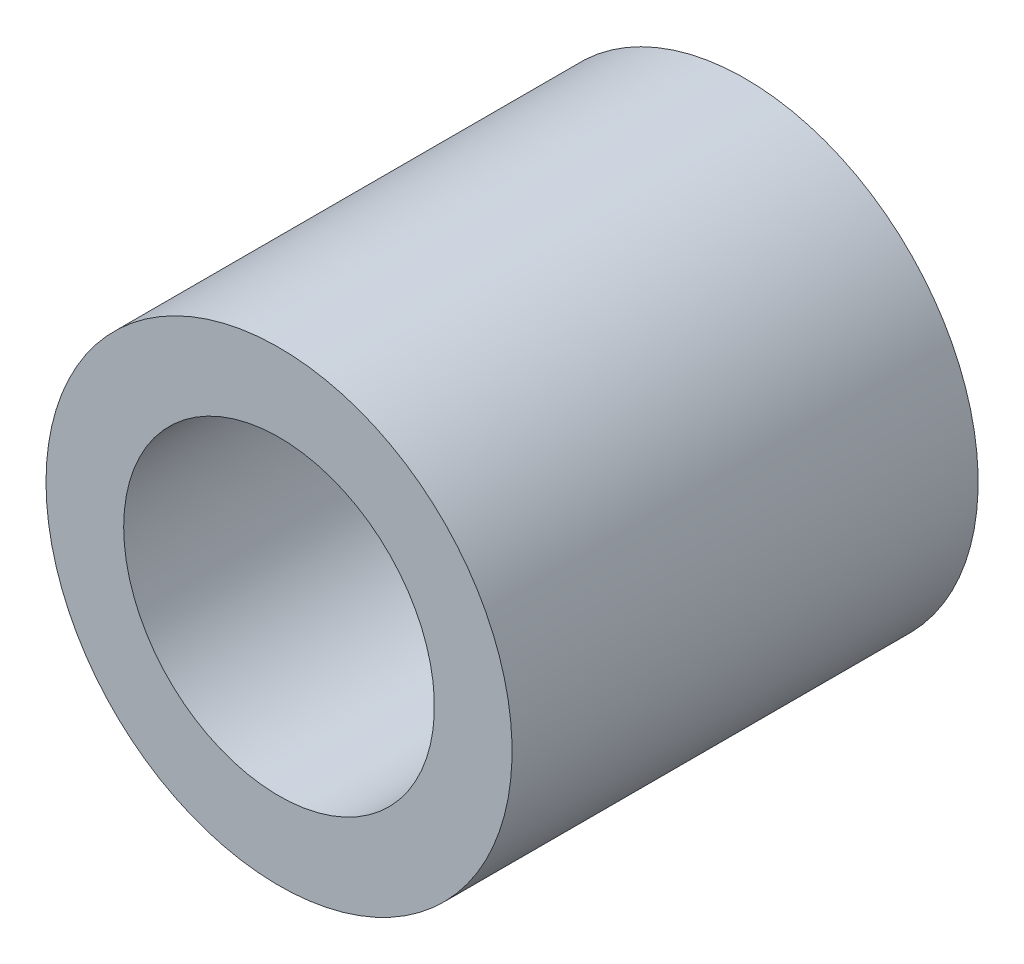
SolidWorks part; units mm, degrees
ref_plane "Front Plane" through (0, 0, 0) normal (0, 0, 1) x (1, 0, 0)
ref_plane "Top Plane" through (0, 0, 0) normal (0, 1, 0) x (1, 0, 0)
ref_plane "Right Plane" through (0, 0, 0) normal (1, 0, 0) x (0, 0, -1)
sketch "Sketch1" plane through (0, 0, 0) normal (0, 0, 1) x (1, 0, 0)
  circle A0 centre (0, 0) radius 12.7
  circle A1 centre (0, 0) radius 19.05
  dimension "D1" = 25.4
  dimension "D2" = 38.1
extrude "Boss-Extrude1" add sketch "Sketch1" along normal blind 38.1 contours A1
